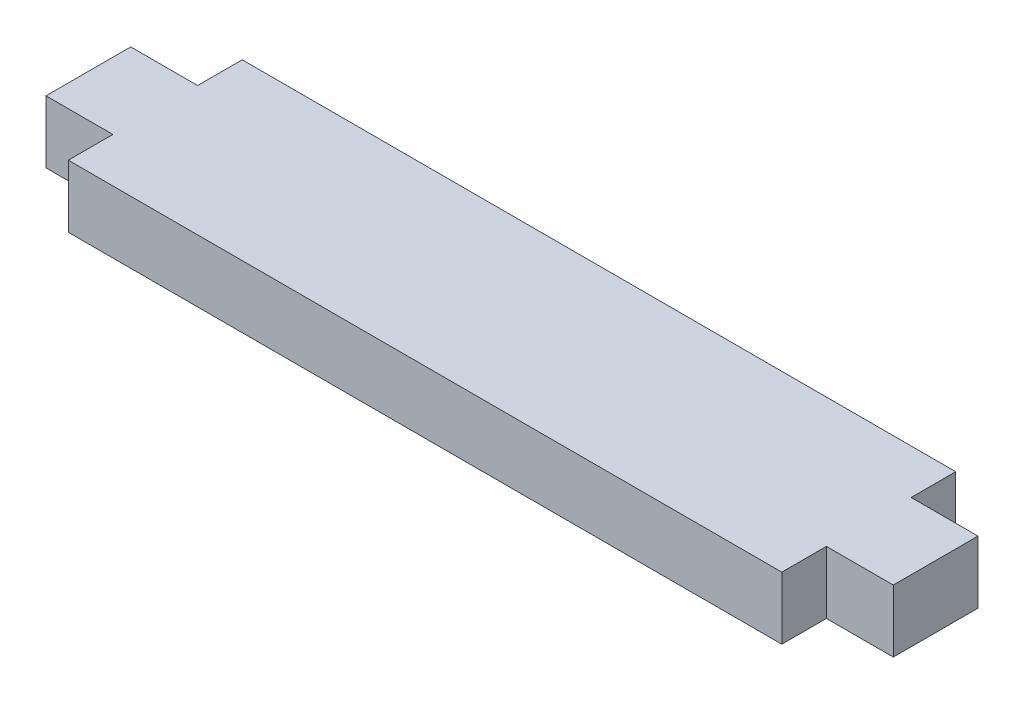
SolidWorks part; units mm, degrees
ref_plane "Front Plane" through (0, 0, 0) normal (0, 0, 1) x (1, 0, 0)
ref_plane "Top Plane" through (0, 0, 0) normal (0, 1, 0) x (1, 0, 0)
ref_plane "Right Plane" through (0, 0, 0) normal (1, 0, 0) x (0, 0, -1)
sketch "Sketch2" plane through (0, 0, 0) normal (0, 0, 1) x (1, 0, 0)
  line L1 (0, 0) -> (80, 0)
  line L2 (0, 0) -> (0, -7)
  line L3 (0, -7) -> (80, -7)
  line L4 (80, 0) -> (80, -7)
  dimension "D1" = 80
  dimension "D2" = 7
extrude "Boss-Extrude1" add sketch "Sketch2" along normal blind 19.5
sketch "Sketch3" plane through (0, 0, 0) normal (0, 1, 0) x (1, 0, 0)
  line L0 (0, -19.5) -> (0, 0) construction
  line L1 (0, -5) -> (-7.5, -5)
  line L2 (0, -5) -> (0, -14.5)
  line L3 (0, -14.5) -> (-7.5, -14.5)
  line L4 (-7.5, -5) -> (-7.5, -14.5)
  line L5 (80, 0) -> (0, 0) construction
  line L6 (80, -19.5) -> (0, -19.5) construction
  line L7 (40, 0) -> (40, -48.1333) construction
  line L8 (87.5, -5) -> (87.5, -14.5)
  line L9 (80, -14.5) -> (87.5, -14.5)
  line L10 (80, -5) -> (80, -14.5)
  line L11 (80, -5) -> (87.5, -5)
  dimension "D1" = 5
  dimension "D2" = 5
  dimension "D3" = 7.5
extrude "Boss-Extrude2" add sketch "Sketch3" against normal blind 7
